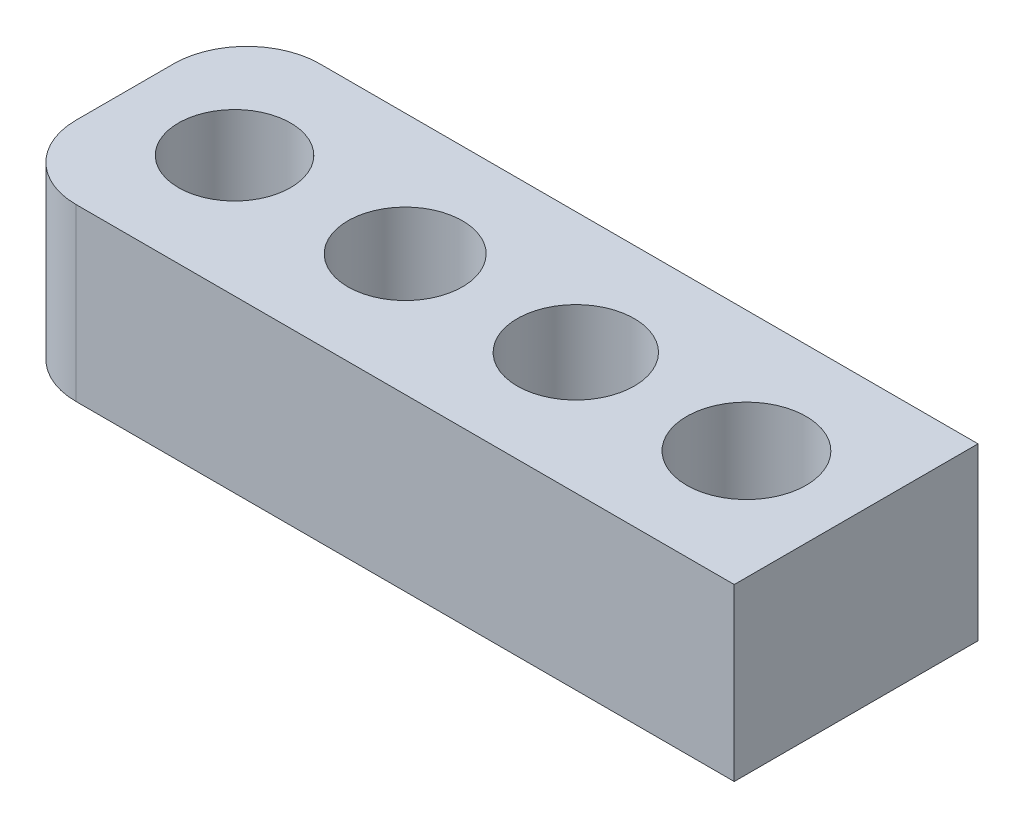
SolidWorks part; units mm, degrees
ref_plane "Front Plane" through (0, 0, 0) normal (0, 0, 1) x (1, 0, 0)
ref_plane "Top Plane" through (0, 0, 0) normal (0, 1, 0) x (1, 0, 0)
ref_plane "Right Plane" through (0, 0, 0) normal (1, 0, 0) x (0, 0, -1)
sketch "Sketch1" plane through (0, 0, 0) normal (0, 1, 0) x (1, 0, 0)
  line L0 (4.5, 5) -> (30.7209, 5) construction
  line L1 (0, 0) -> (30, 0)
  line L2 (0, 0) -> (0, 10)
  line L3 (0, 10) -> (30, 10)
  line L4 (30, 0) -> (30, 10)
  circle A0 centre (4.5, 5) radius 2.3
  circle A1 centre (11.5, 5) radius 2.35
  circle A2 centre (18.5, 5) radius 2.4
  circle A3 centre (25.5, 5) radius 2.45
  point P14 (0, 5)
  dimension "D1" = 4.6
  dimension "D2" = 4.7
  dimension "D3" = 4.8
  dimension "D4" = 4.9
  dimension "D5" = 7
  dimension "D6" = 7
  dimension "D7" = 7
  dimension "D8" = 4.5
  dimension "D9" = 4.5
  dimension "D10" = 10
extrude "Boss-Extrude1" add sketch "Sketch1" along normal blind 7
fillet "Fillet1" radius 3 2 edges at (0, 3.5, 0) (0, 3.5, -10)
